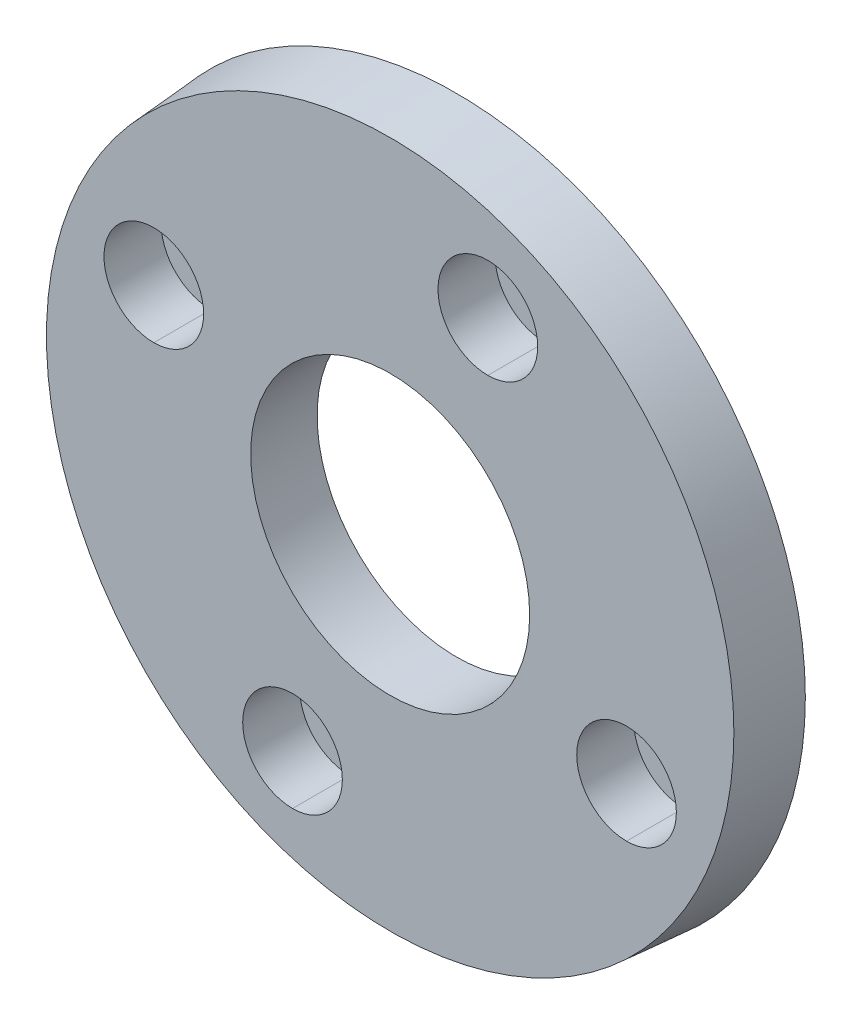
SolidWorks part; units mm, degrees
material "1.0715 (11SMn30)"
ref_plane "Ön Düzlem" through (0, 0, 0) normal (0, 0, 1) x (1, 0, 0)
ref_plane "Üst Düzlem" through (0, 0, 0) normal (0, 1, 0) x (1, 0, 0)
ref_plane "Sağ Düzlem" through (0, 0, 0) normal (1, 0, 0) x (0, 0, -1)
sketch "Çizim1" plane through (0, 0, 0) normal (0, 0, 1) x (1, 0, 0)
  circle A0 centre (0, 0) radius 52.5
  circle A1 centre (0, 0) radius 21
  dimension "D1" = 105
  dimension "D2" = 42
extrude "Yükseklik-Ekstrüzyon1" add sketch "Çizim1" along normal blind 10 draft 4.33
hole_wizard "M8 Altıgen Alyan Başlı Kör Vida İçin Havşa1" positions "Çizim2" profile "Çizim3" size "M8" standard "ISO" slot yes
sketch "Çizim2" plane through (0, 0, 10) normal (0, 0, 1) x (1, 0, 0)
  line L0 (14.7011, 35.5826) -> (14.7012, 35.5826) construction
  point P0 (14.7012, 35.5826)
  point P5 (-35.5826, 14.7012)
  point P8 (-14.7012, -35.5826)
  point P11 (35.5826, -14.7012)
sketch "Çizim3" plane through (14.7012, 35.5826, 10) normal (1, 0, 0) x (0, -1, 0)
  line L0 (0, 0) -> (0, 24.9539)
  line L1 (0, 24.9539) -> (4.5, 22.25)
  line L2 (4.5, 22.25) -> (4.5, 8.6)
  line L3 (4.5, 8.6) -> (7.5, 8.6)
  line L4 (7.5, 8.6) -> (7.5, 0)
  line L5 (7.5, 0) -> (0, 0)
  line L10 (0, 24.9539) -> (-4.5, 22.25) construction
  line L11 (0, -6.35) -> (0, 107.95) construction
  dimension "Hole Dia." = 9
  dimension "Hole Depth" = 22.25
  dimension "C'Bore Dia." = 15
  dimension "C'Bore Depth" = 8.6
  dimension "Drill Angle" = 118
sketch "Çizim4" plane through (0, 0, 0) normal (0, 0, 1) x (1, 0, 0)
  circle A0 centre (0, 0) radius 21 construction
  circle A1 centre (0, 0) radius 21
  circle A2 centre (0, 0) radius 22
  dimension "D1" = 1
extrude "Yükseklik-Ekstrüzyon2" add sketch "Çizim4" along normal up to vertex (10 mm away)
